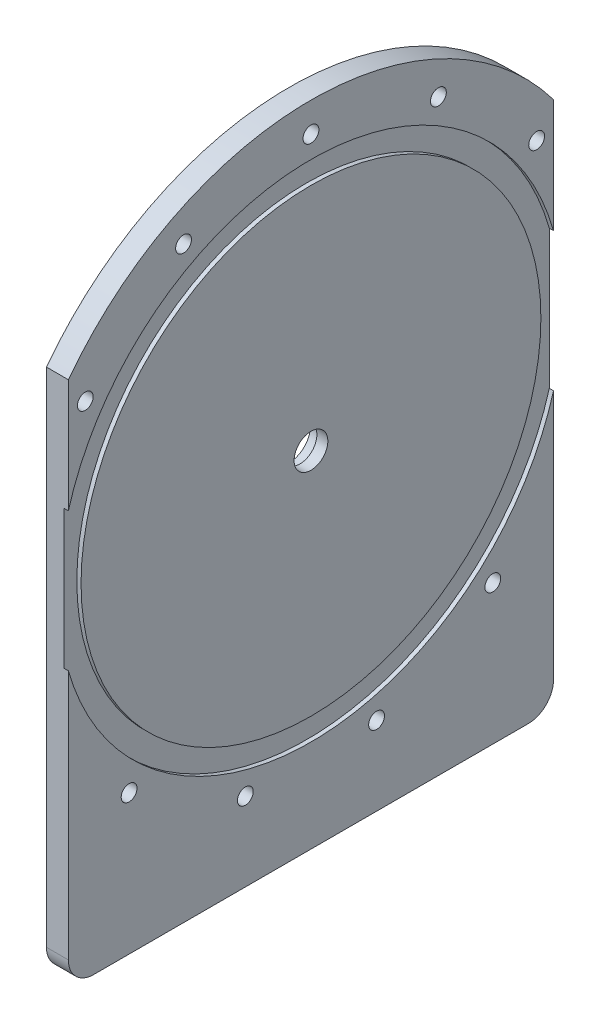
SolidWorks part; units mm, degrees
material "6061 Alloy"
ref_plane "Front Plane" through (0, 0, 0) normal (0, 0, 1) x (1, 0, 0)
ref_plane "Top Plane" through (0, 0, 0) normal (0, 1, 0) x (1, 0, 0)
ref_plane "Right Plane" through (0, 0, 0) normal (1, 0, 0) x (0, 0, -1)
sketch "Sketch1" plane through (0, 0, 0) normal (1, 0, 0) x (0, 0, -1)
  line L0 (0, -1000) -> (0, 49000) construction
  line L1 (5.5562, 0) -> (2.7781, 4.8119) construction
  line L2 (2.7781, 4.8119) -> (-2.7781, 4.8119) construction
  line L3 (-2.7781, 4.8119) -> (-5.5562, 0) construction
  line L4 (-5.5562, 0) -> (-2.7781, -4.8119) construction
  line L5 (-2.7781, -4.8119) -> (2.7781, -4.8119) construction
  line L6 (2.7781, -4.8119) -> (5.5562, 0) construction
  line L7 (-65.405, -103.8551) -> (65.405, -103.8551)
  line L8 (-73.025, -96.2351) -> (-73.025, -69.997)
  line L10 (73.025, -96.2351) -> (73.025, -69.997)
  circle A0 centre (0, 0) radius 69.85 construction
  circle A1 centre (0, 0) radius 76.2 construction
  circle A2 centre (0, 0) radius 5.08
  circle A3 centre (0, 0) radius 3.9688 construction
  arc A4 (79.6018, -44.9981) -> (-79.6018, -44.9981) centre (0, 0) ccw
  circle A5 centre (0, 0) radius 11.5094 construction
  circle A6 centre (0, 0) radius 91.44 construction
  arc A7 (65.405, -103.8551) -> (73.025, -96.2351) centre (65.405, -96.2351) ccw
  arc A8 (-65.405, -103.8551) -> (-73.025, -96.2351) centre (-65.405, -96.2351) cw
  arc A9 (79.6018, -44.9981) -> (73.025, -69.997) centre (123.825, -69.997) ccw
  arc A10 (-73.025, -69.997) -> (-79.6018, -44.9981) centre (-123.825, -69.997) ccw
  point P19 (73.025, -103.8551)
  point P26 (-73.025, -103.8551)
  dimension "D1" = 152.4
  dimension "D2" = 139.7
  dimension "D3" = 10.16
  dimension "D4" = 7.9375
  dimension "D5" = 15.24
  dimension "D6" = 23.0188
  dimension "D8" = 7.62
  dimension "D9" = 50.8
  dimension "D7" = 146.05
extrude "Boss-Extrude1" add sketch "Sketch1" along normal blind 6.604
sketch "Sketch2" plane through (0, 0, 0) normal (1, 0, 0) x (0, 0, -1)
  circle A0 centre (0, 0) radius 6.35 construction
  circle A1 centre (0, 0) radius 6.477
  dimension "D1" = 12.7
  dimension "D2" = 12.954
extrude "Cut-Extrude1" cut sketch "Sketch2" along direction (1, 0, 0) on the side of the normal blind 3.302
sketch "Sketch3" plane through (6.604, 0, 0) normal (1, 0, 0) x (0, 0, -1)
  circle A0 centre (0, 0) radius 75.946
  circle A1 centre (0, 0) radius 69.215
  dimension "D2" = 138.43
  dimension "D1" = 6.731
extrude "Cut-Extrude2" cut sketch "Sketch3" against normal blind 1.27
sketch "Sketch4" plane through (0, 0, 0) normal (-1, 0, 0) x (0, 0, 1)
  line L0 (0, -1000) -> (0, 49000) construction
  line L1 (-1000, 0) -> (49000, 0) construction
  circle A0 centre (-54.7408, -61.7896) radius 2.3813
  circle A1 centre (0, 82.55) radius 2.3812
  circle A2 centre (-77.1856, -29.2726) radius 2.3813
  circle A3 centre (0, 0) radius 82.55 construction
  circle A4 centre (38.3629, 73.0944) radius 2.3813
  circle A5 centre (67.9373, 46.8937) radius 2.3813
  circle A6 centre (81.9481, 9.9503) radius 2.3813
  circle A7 centre (77.1856, -29.2726) radius 2.3813
  circle A8 centre (54.7408, -61.7896) radius 2.3813
  circle A9 centre (19.7555, -80.1512) radius 2.3812
  circle A10 centre (-19.7555, -80.1512) radius 2.3812
  circle A11 centre (-81.9481, 9.9503) radius 2.3812
  circle A12 centre (-67.9373, 46.8937) radius 2.3813
  circle A13 centre (-38.3629, 73.0944) radius 2.3812
  point P34 (0, 0)
  dimension "D2" = 13
extrude "Cut-Extrude3" cut sketch "Sketch4" against normal through all
sketch "Sketch5" plane through (0, 0, 0) normal (-1, 0, 0) x (0, 0, 1)
  circle A0 centre (0, 82.55) radius 3.7783
  circle A1 centre (-83.1242, 18.8058) radius 3.7783
  circle A2 centre (-66.2663, 52.1748) radius 3.7783
  circle A3 centre (36.2836, 73.5401) radius 3.7783
  circle A5 centre (-36.5996, 74.9248) radius 3.7783
  circle A6 centre (65.0647, 49.6796) radius 3.7783
  circle A7 centre (80.6429, 15.6943) radius 3.7783
  circle A8 centre (79.9327, -21.6844) radius 3.7783
  circle A9 centre (63.0748, -55.0534) radius 3.7783
  circle A10 centre (33.4081, -77.8035) radius 3.7783
  circle A11 centre (-3.1915, -85.4286) radius 3.7783
  circle A12 centre (-39.4751, -76.4187) radius 3.7783
  circle A13 centre (-68.2562, -52.5582) radius 3.7783
  circle A14 centre (-83.8344, -18.573) radius 3.7783
  point P29 (-1.5957, -1.4393)
  dimension "D1" = 14
extrude "Cut-Extrude4" [suppressed] cut sketch "Sketch5" against normal blind 1.27
sketch "Sketch6" plane through (6.604, 0, 0) normal (1, 0, 0) x (0, 0, -1)
  line L0 (-73.025, -69.997) -> (-73.025, 55.0329)
  line L1 (-73.025, 55.0329) -> (-110.5376, 55.0329)
  line L2 (-110.5376, 55.0329) -> (-110.5376, -69.997)
  line L3 (-110.5376, -69.997) -> (-73.025, -69.997)
  line L4 (73.025, -69.997) -> (73.025, 55.0329)
  line L5 (73.025, 55.0329) -> (102.9616, 55.0329)
  line L6 (102.9616, 55.0329) -> (102.9616, -69.997)
  line L7 (102.9616, -69.997) -> (73.025, -69.997)
  arc A1 (79.6018, -44.9981) -> (-79.6018, -44.9981) centre (0, 0) ccw construction
extrude "Cut-Extrude6" cut sketch "Sketch6" against normal through all contours L1 L2 L3 L0 | L5 L6 L7 L4
